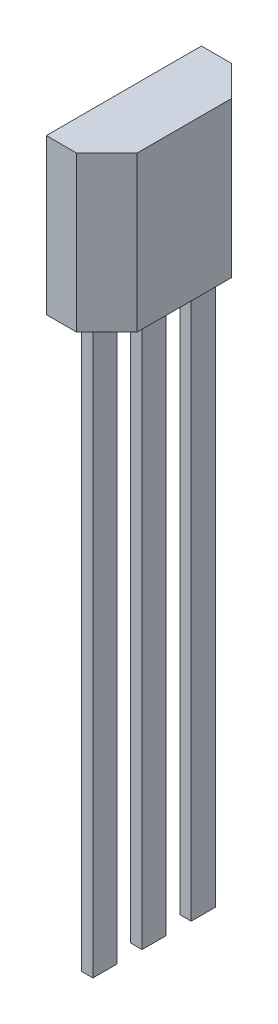
SolidWorks part; units mm, degrees
ref_plane "Front Plane" through (0, 0, 0) normal (0, 0, 1) x (1, 0, 0)
ref_plane "Top Plane" through (0, 0, 0) normal (0, 1, 0) x (1, 0, 0)
ref_plane "Right Plane" through (0, 0, 0) normal (1, 0, 0) x (0, 0, -1)
sketch "Sketch4" plane through (0, 0, 0) normal (0, 1, 0) x (1, 0, 0)
  line L0 (0.8, 2.05) -> (1.6, 1.25)
  line L1 (0, 2.05) -> (0.8, 2.05)
  line L2 (0, 2.05) -> (0, -2.05)
  line L3 (0, -2.05) -> (0.8, -2.05)
  line L5 (1.6, 1.25) -> (1.6, -1.25)
  line L6 (1.6, -1.25) -> (0.8, -2.05)
  point P4 (0, 0)
  point P7 (0, 0)
  dimension "D1" = 4.1
  dimension "D2" = 135
  dimension "D3" = 135
  dimension "D4" = 2.5
  dimension "D5" = 1.6
extrude "Boss-Extrude3" add sketch "Sketch4" along normal blind 2.4 and the other way blind 1.7
sketch "Sketch5" plane through (0, -1.7, 0) normal (0, -1, 0) x (1, 0, 0)
  line L0 (0.5, 1.62) -> (0.5, 0.98)
  line L1 (0.5, 0.32) -> (0.8, 0.32)
  line L2 (0.5, 0.32) -> (0.5, -0.32)
  line L3 (0.5, -0.32) -> (0.8, -0.32)
  line L4 (0.8, 0.32) -> (0.8, -0.32)
  line L5 (0.5, 0.32) -> (0.8, -0.32) construction
  line L6 (0.5, -0.32) -> (0.8, 0.32) construction
  line L7 (0.5, 1.62) -> (0.8, 1.62)
  line L8 (0.8, 1.62) -> (0.8, 0.98)
  line L9 (0.5, 0.98) -> (0.8, 0.98)
  line L10 (0.5, 0.32) -> (0.5, -0.32) [skipped]
  line L11 (0.5, 0.32) -> (0.8, 0.32) [skipped]
  line L12 (0.8, 0.32) -> (0.8, -0.32) [skipped]
  line L13 (0.5, -0.32) -> (0.8, -0.32) [skipped]
  line L14 (0.5, -0.98) -> (0.5, -1.62)
  line L15 (0.5, -0.98) -> (0.8, -0.98)
  line L16 (0.8, -0.98) -> (0.8, -1.62)
  line L17 (0.5, -1.62) -> (0.8, -1.62)
  point P0 (0.65, 0)
  point P5 (0, 0)
  point P6 (0.65, -0.98)
  dimension "D1" = 0.3
  dimension "D2" = 0.64
  dimension "D3" = 2
  dimension "D5" = 0.66
  dimension "D6" = 0.66
  dimension "D4" = 2
extrude "Boss-Extrude4" add sketch "Sketch5" along normal blind 15
